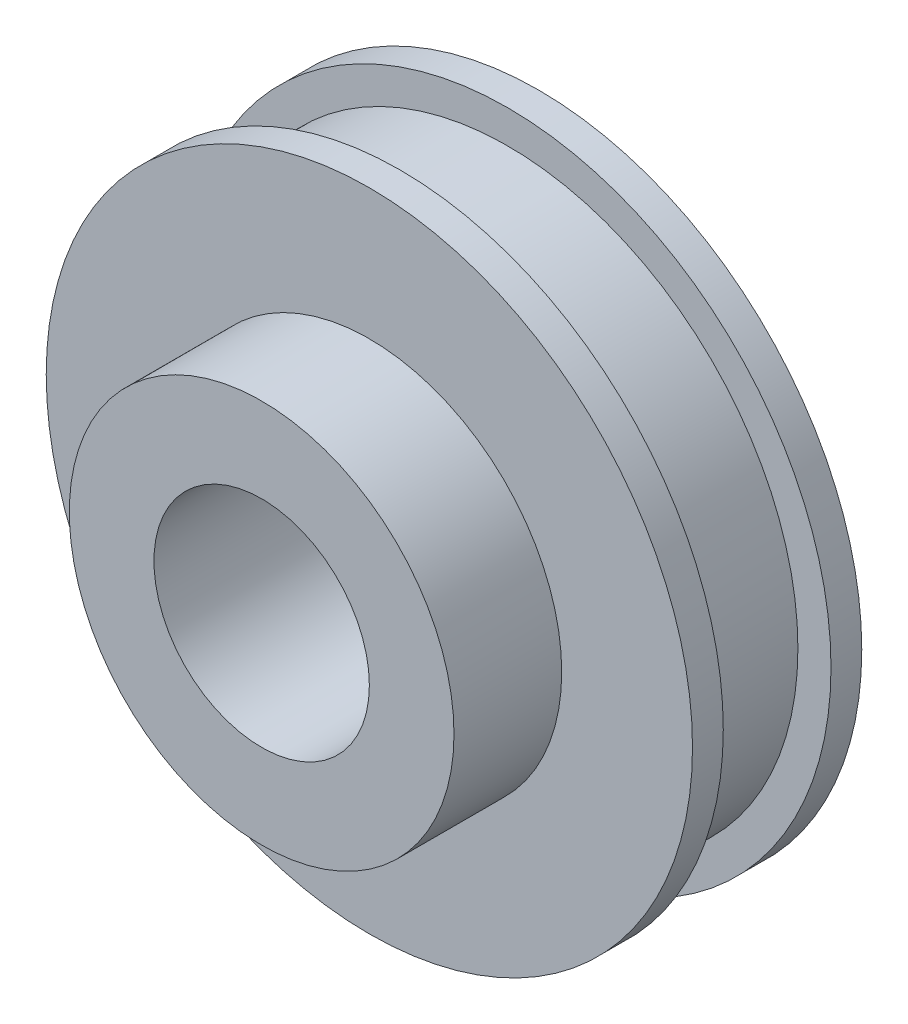
SolidWorks part; units mm, degrees
ref_plane "前视基准面" through (0, 0, 0) normal (0, 0, 1) x (1, 0, 0)
ref_plane "上视基准面" through (0, 0, 0) normal (0, 1, 0) x (1, 0, 0)
ref_plane "右视基准面" through (0, 0, 0) normal (1, 0, 0) x (0, 0, -1)
other "Configuration Table"
sketch "草图1" plane through (0, 0, 0) normal (0, 0, 1) x (1, 0, 0)
  circle A0 centre (0, 0) radius 21
  dimension "D1" = 42
extrude "凸台-拉伸1" add sketch "草图1" along normal blind 2
sketch "草图2" plane through (0, 0, 2) normal (0, 0, 1) x (1, 0, 0)
  circle A0 centre (0, 0) radius 18.85
  dimension "D1" = 37.7
extrude "凸台-拉伸2" add sketch "草图2" along normal blind 7
sketch "草图3" plane through (0, 0, 9) normal (0, 0, 1) x (1, 0, 0)
  circle A1 centre (0, 0) radius 21
  circle A2 centre (0, 0) radius 21
  dimension "D1" = 0
extrude "凸台-拉伸3" add sketch "草图3" along normal blind 2
sketch "草图4" plane through (0, 0, 11) normal (0, 0, 1) x (1, 0, 0)
  circle A0 centre (0, 0) radius 12.5
extrude "凸台-拉伸4" add sketch "草图4" along normal blind 7
sketch "草图5" plane through (0, 0, 18) normal (0, 0, 1) x (1, 0, 0)
  circle A0 centre (0, 0) radius 7
extrude "切除-拉伸1" cut sketch "草图5" against normal through all
